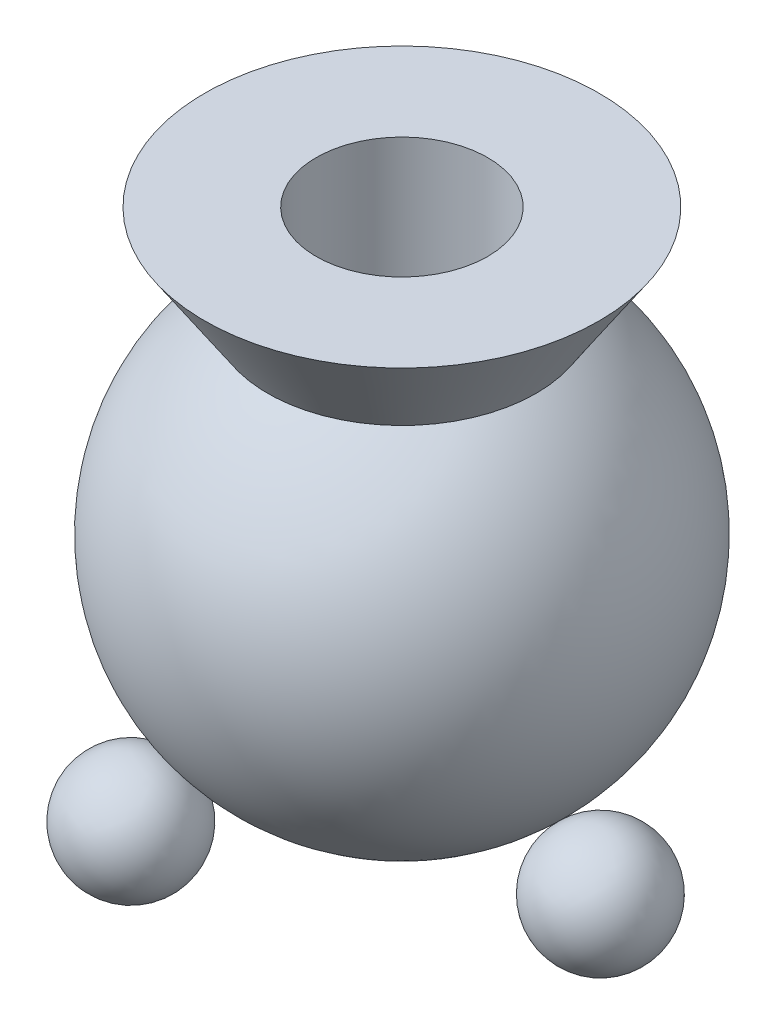
SolidWorks part; units mm, degrees
ref_plane "Front Plane" through (0, 0, 0) normal (0, 0, 1) x (1, 0, 0)
ref_plane "Top Plane" through (0, 0, 0) normal (0, 1, 0) x (1, 0, 0)
ref_plane "Right Plane" through (0, 0, 0) normal (1, 0, 0) x (0, 0, -1)
sketch "Sketch1" plane through (0, 0, 0) normal (0, 0, 1) x (1, 0, 0)
  line L0 (0, 0) -> (0, 40)
  line L1 (10, 60) -> (23, 60)
  line L2 (23, 60) -> (15.6525, 49)
  line L6 (0, 40) -> (10, 40)
  line L7 (10, 60) -> (10, 40)
  arc A0 (0, 0) -> (15.6525, 49) centre (0, 27) ccw
  dimension "D3" = 27
  dimension "D1" = 11
  dimension "D2" = 13
  dimension "D4" = 56.259
  dimension "D5" = 10
  dimension "D6" = 20
revolve "Revolve1" add sketch "Sketch1" angle 360 about L0
sketch "Sketch2" plane through (0, 0, 0) normal (0, 0, 1) x (1, 0, 0)
  line L0 (0, 27) -> (27.8711, -2.8823) construction
  line L1 (18.4159, 7.2552) -> (27.8711, -2.8823)
  arc A0 (27.8711, -2.8823) -> (18.4159, 7.2552) centre (23.1435, 2.1865) ccw
  arc A1 (-15.6525, 49) -> (15.6525, 49) centre (0, 27) ccw construction
revolve "Revolve2" add sketch "Sketch2" angle 360 about L1
pattern_circular "CirPattern1" count 3 over 360 about axis through (0, 0, 0) along (0, 1, 0) of bodies 102
